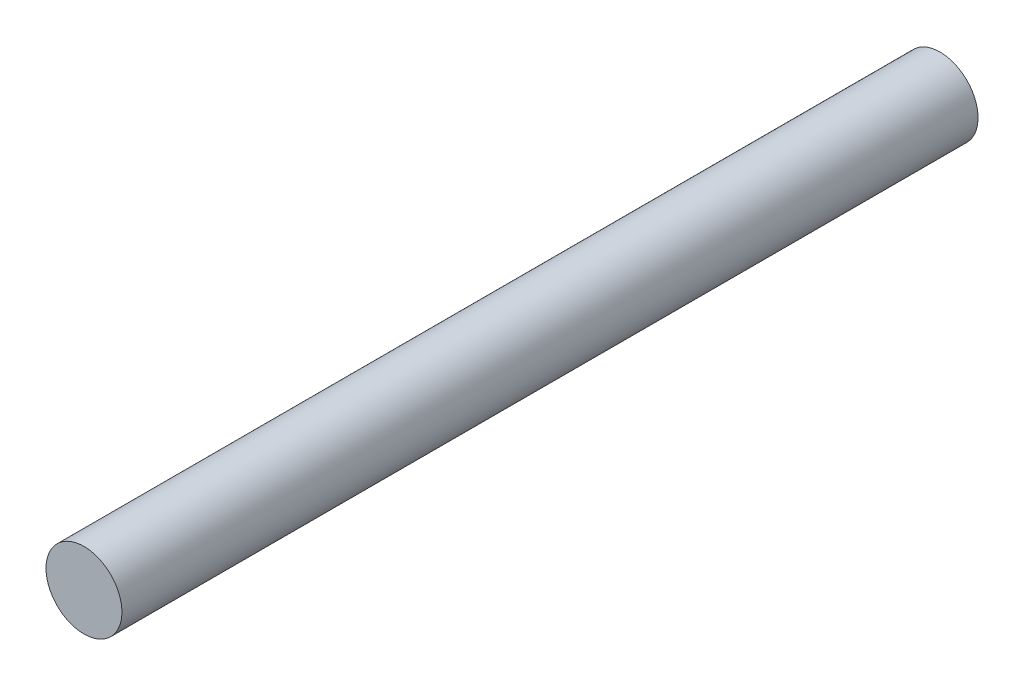
SolidWorks part; units mm, degrees
ref_plane "Front Plane" through (0, 0, 0) normal (0, 0, 1) x (1, 0, 0)
ref_plane "Top Plane" through (0, 0, 0) normal (0, 1, 0) x (1, 0, 0)
ref_plane "Right Plane" through (0, 0, 0) normal (1, 0, 0) x (0, 0, -1)
sketch "Sketch1" plane through (0, 0, 0) normal (0, 0, 1) x (1, 0, 0)
  circle A0 centre (0, 0) radius 3.3782
  dimension "D1" = 6.7564
extrude "Boss-Extrude1" add sketch "Sketch1" along normal blind 76.2
